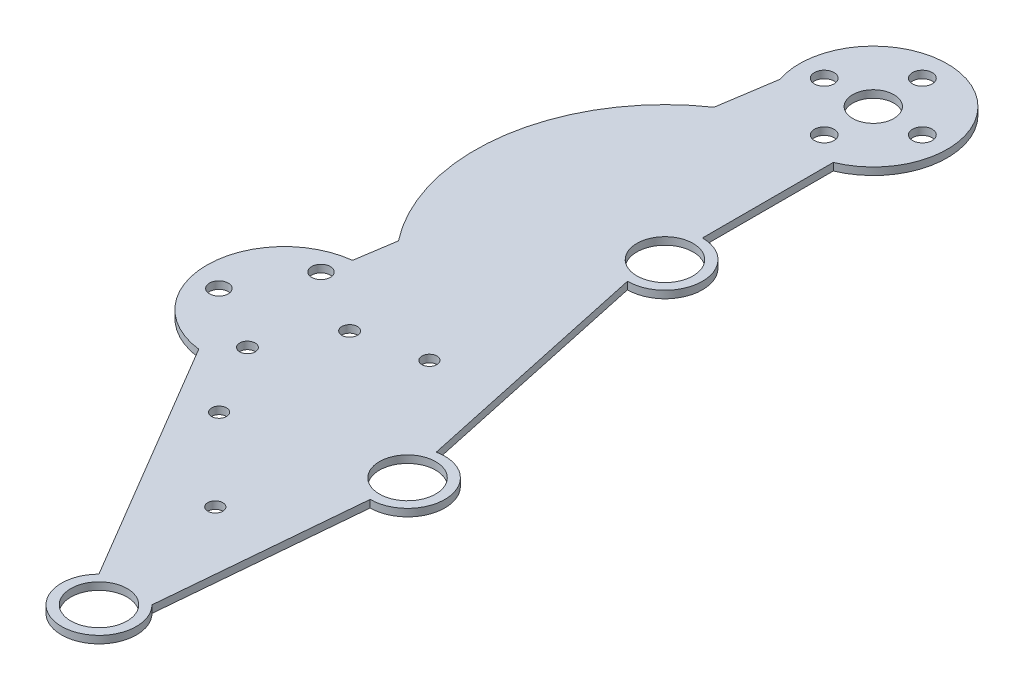
SolidWorks part; units mm, degrees
ref_plane "Front" through (0, 0, 0) normal (0, 0, 1) x (1, 0, 0)
ref_plane "Top" through (0, 0, 0) normal (0, 1, 0) x (1, 0, 0)
ref_plane "Right" through (0, 0, 0) normal (1, 0, 0) x (0, 0, -1)
sketch "Sketch1" plane through (0, 0, 0) normal (0, 1, 0) x (1, 0, 0)
  line L0 (15.9743, 29.6759) -> (13.4124, 22.7054)
  line L1 (59.4628, -19.5789) -> (55.6662, -62.316)
  line L2 (44.3338, -62.316) -> (13.4124, -10.0901)
  line L3 (46.6071, 96.669) -> (46.6071, 64.169)
  line L4 (46.6071, 48.169) -> (57.7856, -3.8043)
  circle A1 centre (46.6071, 56.169) radius 6
  circle A2 centre (59.4628, -11.6024) radius 6
  circle A3 centre (50, -67.9636) radius 6
  circle A4 centre (46.6071, 56.169) radius 40.5
  circle A5 centre (15.2468, 6.3076) radius 16.5
  circle A6 centre (18.2954, -4.5876) radius 1.65
  circle A7 centre (26.142, 9.3563) radius 1.65
  circle A8 centre (12.1981, 17.2029) radius 2
  circle A9 centre (4.3515, 3.259) radius 2
  circle A10 centre (44.3338, -37.4884) radius 1.6
  circle A11 centre (59.4628, -11.6024) radius 7.9765
  circle A12 centre (50, -67.9636) radius 8
  circle A13 centre (46.6071, 56.169) radius 8
  circle A14 centre (27.2332, -19.5789) radius 1.6
  circle A15 centre (40.0896, 12.4397) radius 1.6
  dimension "D1" = 82
  dimension "D2" = 12
  dimension "D3" = 12
  dimension "D4" = 12
  dimension "D6" = 57.15
  dimension "D7" = 33
  dimension "D9" = 81
  dimension "D5" = 68.98
extrude "Boss-Extrude2" add sketch "Sketch1" along normal blind 1.5875
sketch "Sketch2" plane through (0, 1.5875, 0) normal (0, 1, 0) x (1, 0, 0)
  circle A0 centre (40.5463, 106.6726) radius 16.1315
sketch "Sketch3" plane through (0, 1.5875, 0) normal (0, 1, 0) x (1, 0, 0)
  line L0 (13.4124, 22.7054) -> (25.5511, 101.703)
  line L1 (46.6071, 64.169) -> (46.6071, 92.0844)
  line L2 (46.6071, 96.669) -> (46.6071, 64.169) construction
  line L3 (46.6071, 64.169) -> (36.5959, 64.169)
  line L4 (36.5959, 64.169) -> (13.4124, 22.7054)
  circle A0 centre (40.5463, 106.6726) radius 15.7972
  line M1 (15.9743, 29.6759) -> (13.4124, 22.7054)
  line M9 (46.6071, 64.169) -> (46.6071, 96.669)
  arc M10 (46.6071, 96.669) -> (15.9743, 29.6759) centre (46.6071, 56.169) ccw
extrude "Boss-Extrude3" add sketch "Sketch3" against normal blind 1.5875 contours A0 M9 M10 | A0 L0 M10 | L0 M1 M10
sketch "Sketch4" plane through (0, 1.5875, 0) normal (0, 1, 0) x (1, 0, 0)
  circle A4 centre (40.5463, 106.6726) radius 4.4
  circle A6 centre (40.5463, 117.1402) radius 2.1
  circle A7 centre (30.0786, 106.6726) radius 2.1
  circle A8 centre (51.0139, 106.6726) radius 2.1
  circle A9 centre (40.5463, 96.205) radius 2.1
extrude "Cut-Extrude1" cut sketch "Sketch4" against normal blind 1.5875
